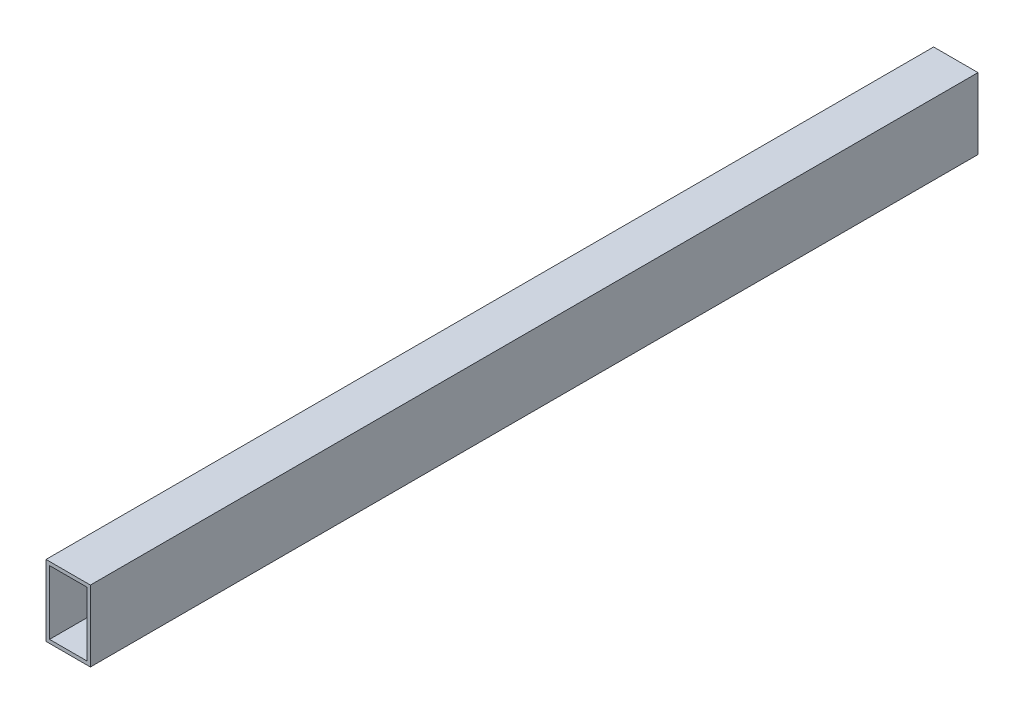
SolidWorks part; units mm, degrees
ref_plane "Front Plane" through (0, 0, 0) normal (0, 0, 1) x (1, 0, 0)
ref_plane "Top Plane" through (0, 0, 0) normal (0, 1, 0) x (1, 0, 0)
ref_plane "Right Plane" through (0, 0, 0) normal (1, 0, 0) x (0, 0, -1)
sketch "Sketch1" plane through (0, 0, 0) normal (0, 0, 1) x (1, 0, 0)
  line L1 (-25, 40) -> (25, 40)
  line L2 (-25, 40) -> (-25, -40)
  line L3 (-25, -40) -> (25, -40)
  line L4 (25, 40) -> (25, -40)
  point P0 (0, 0)
  point P7 (0, 0)
  dimension "D1" = 80
  dimension "D2" = 50
extrude "Boss-Extrude1" add sketch "Sketch1" along normal blind 1000 contours L1 L4 L3 L2
sketch "Sketch2" plane through (0, 0, 0) normal (0, 0, -1) x (-1, 0, 0)
  line L1 (-21, 36) -> (21, 36)
  line L2 (-21, 36) -> (-21, -36)
  line L3 (-21, -36) -> (21, -36)
  line L4 (21, 36) -> (21, -36)
  line L5 (-21, 36) -> (21, -36) construction
  line L6 (-21, -36) -> (21, 36) construction
  point P0 (0, 0)
  dimension "D1" = 42
  dimension "D2" = 72
extrude "Cut-Extrude1" cut sketch "Sketch2" against normal blind 1000
